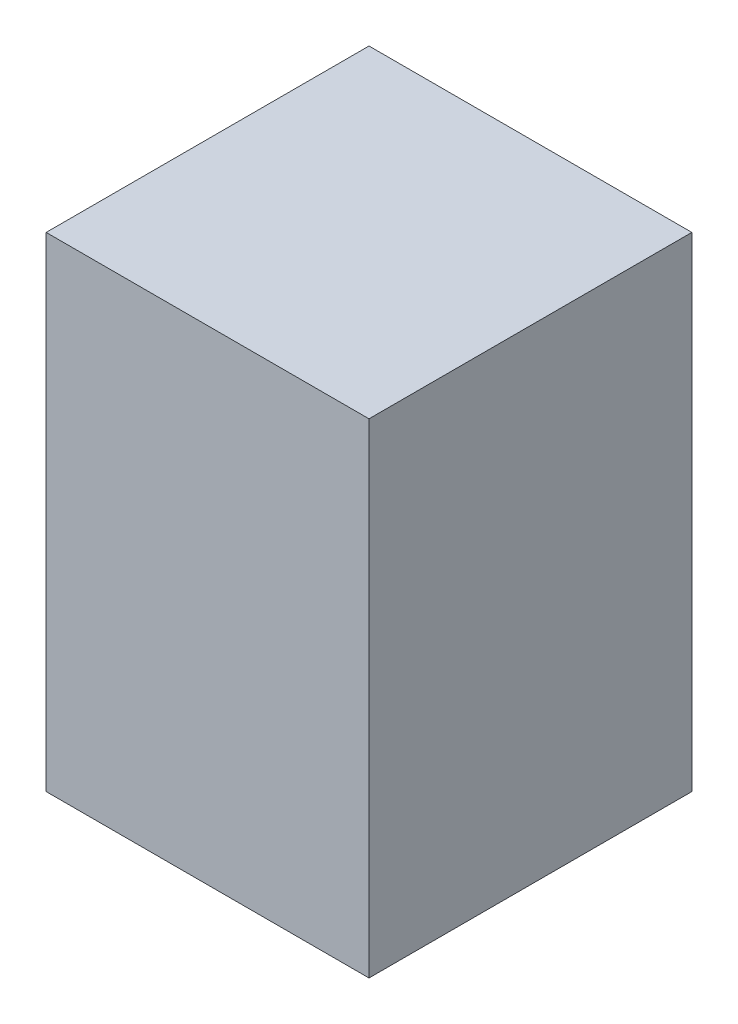
SolidWorks part; units mm, degrees
other "Markup1"
sketch "Sketch4" plane through (0, 750, 0) normal (-0.3936, 0.2648, -0.8803) x (-0.8349, 0.2978, 0.4628)
ref_plane "Front Plane" through (0, 0, 0) normal (0, 0, 1) x (1, 0, 0)
ref_plane "Top Plane" through (0, 0, 0) normal (0, 1, 0) x (1, 0, 0)
ref_plane "Right Plane" through (0, 0, 0) normal (1, 0, 0) x (0, 0, -1)
sketch "Sketch1" plane through (0, 0, 0) normal (0, 0, 1) x (1, 0, 0)
  line L1 (0, 0) -> (500, 0)
  line L2 (0, 0) -> (0, 750)
  line L3 (0, 750) -> (500, 750)
  line L4 (500, 0) -> (500, 750)
  line L5 (12, 12) -> (488, 12)
  line L6 (12, 12) -> (12, 738)
  line L7 (12, 738) -> (488, 738)
  line L8 (488, 12) -> (488, 738)
  dimension "D1" = 500
  dimension "D2" = 750
  dimension "D3" = 12
  dimension "D4" = 12
  dimension "D5" = 12
  dimension "D6" = 12
extrude "Boss-Extrude1" add sketch "Sketch1" along normal blind 500 contours L2 L3 L4 L1
sketch "Sketch2" plane through (0, 0, 0) normal (0, 0, -1) x (-1, 0, 0)
  line L0 (-500, 0) -> (-500, 750) construction
  line L1 (-488, 738) -> (-12, 738)
  line L2 (-488, 738) -> (-488, 12)
  line L3 (-488, 12) -> (-12, 12)
  line L4 (-12, 738) -> (-12, 12)
  line L5 (0, 750) -> (-500, 750) construction
  line L6 (0, 0) -> (0, 750) construction
  line L7 (0, 0) -> (-500, 0) construction
  dimension "D1" = 12
  dimension "D2" = 12
  dimension "D3" = 12
  dimension "D4" = 12
extrude "Cut-Extrude1" cut sketch "Sketch2" against normal blind 488
sketch "Sketch3" plane through (0, 0, 0) normal (0, 0, -1) x (-1, 0, 0)
  line L0 (-488, 738) -> (-488, 12) construction
  line L1 (-494, 257) -> (-488, 257)
  line L2 (-494, 257) -> (-494, 243)
  line L3 (-494, 243) -> (-488, 243)
  line L4 (-488, 257) -> (-488, 243)
  line L5 (0, 0) -> (-500, 0) construction
  line L6 (-488, 738) -> (-488, 12) construction
  line L7 (-494, 507) -> (-488, 507)
  line L8 (-494, 507) -> (-494, 493)
  line L9 (-494, 493) -> (-488, 493)
  line L10 (-488, 507) -> (-488, 493)
  line L11 (-12, 12) -> (-12, 738) construction
  line L12 (-12, 507) -> (-6, 507)
  line L13 (-12, 507) -> (-12, 493)
  line L14 (-12, 493) -> (-6, 493)
  line L15 (-6, 507) -> (-6, 493)
  line L17 (-12, 257) -> (-6, 257)
  line L18 (-12, 257) -> (-12, 243)
  line L19 (-12, 243) -> (-6, 243)
  line L20 (-6, 257) -> (-6, 243)
  point P6 (-494, 250)
  point P15 (-494, 500)
  point P26 (-6, 250)
  point P27 (-6, 500)
  dimension "D1" = 250
  dimension "D2" = 6
  dimension "D3" = 14
  dimension "D4" = 250
  dimension "D5" = 14
  dimension "D6" = 6
  dimension "D7" = 14
  dimension "D8" = 14
  dimension "D9" = 6
  dimension "D10" = 6
  dimension "D11" = 250
  dimension "D12" = 250
extrude "Cut-Extrude2" cut sketch "Sketch3" against normal blind 488
